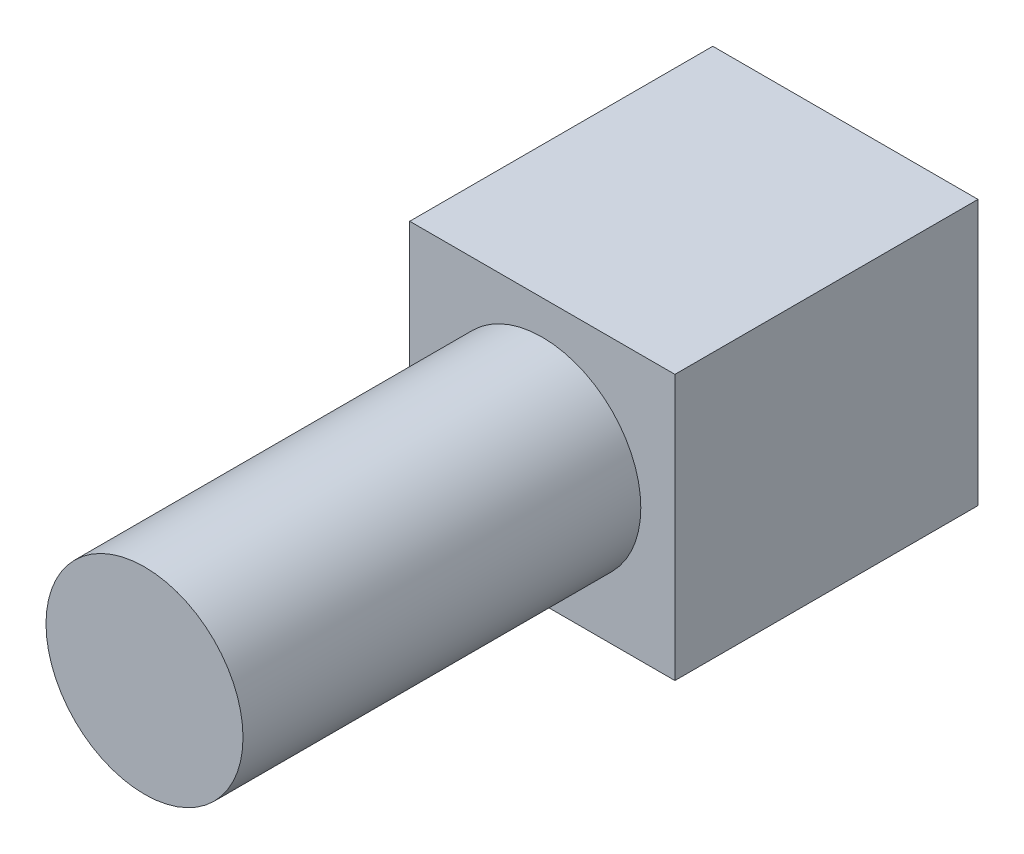
SolidWorks part; units mm, degrees
ref_plane "前视基准面" through (0, 0, 0) normal (0, 0, 1) x (1, 0, 0)
ref_plane "上视基准面" through (0, 0, 0) normal (0, 1, 0) x (1, 0, 0)
ref_plane "右视基准面" through (0, 0, 0) normal (1, 0, 0) x (0, 0, -1)
sketch "草图1" plane through (0, 0, 0) normal (0, 0, 1) x (1, 0, 0)
  line L1 (-3.5, -3.5) -> (3.5, -3.5)
  line L2 (-3.5, -3.5) -> (-3.5, 3.5)
  line L3 (-3.5, 3.5) -> (3.5, 3.5)
  line L4 (3.5, -3.5) -> (3.5, 3.5)
  line L5 (-3.5, -3.5) -> (3.5, 3.5) construction
  line L6 (-3.5, 3.5) -> (3.5, -3.5) construction
  point P0 (0, 0)
  dimension "D1" = 7
  dimension "D2" = 7
sketch "草图2" plane through (0, 0, 0) normal (0, 0, 1) x (1, 0, 0)
  circle A0 centre (0, 0) radius 2.6
  dimension "D1" = 5.2
extrude "凸台-拉伸1" add sketch "草图1" against normal blind 8
extrude "凸台-拉伸2" add sketch "草图2" along normal blind 10.5
